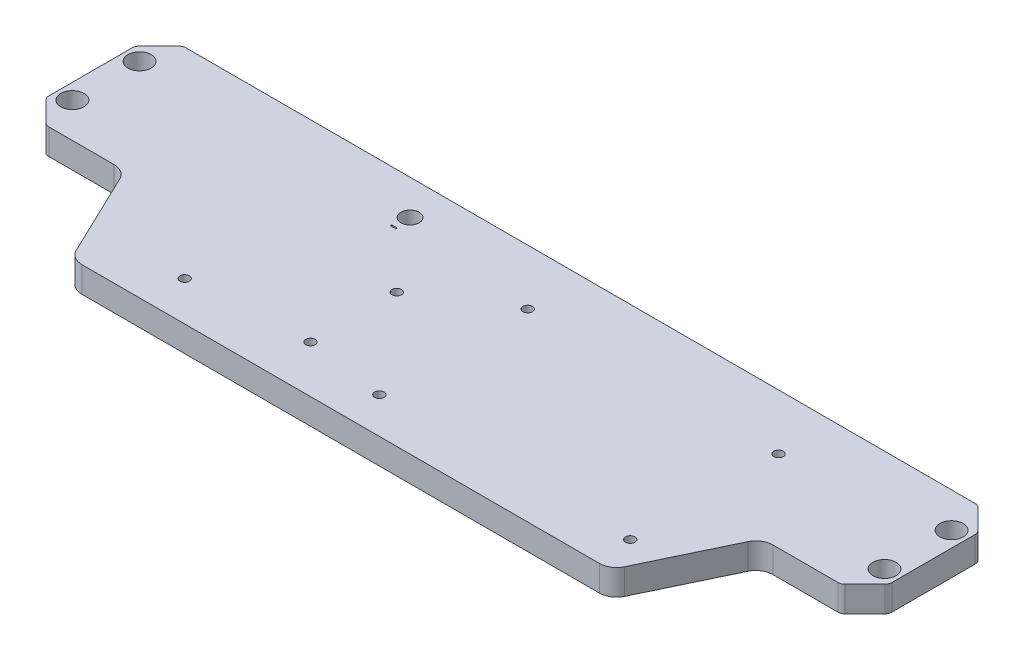
SolidWorks part; units mm, degrees
ref_plane "Front Plane" through (0, 0, 0) normal (0, 0, 1) x (1, 0, 0)
ref_plane "Top Plane" through (0, 0, 0) normal (0, 1, 0) x (1, 0, 0)
ref_plane "Right Plane" through (0, 0, 0) normal (1, 0, 0) x (0, 0, -1)
sketch "Sketch1" plane through (0, 0, 0) normal (0, 1, 0) x (1, 0, 0)
  line L0 (150.5375, 0) -> (-150.5375, 0) construction
  line L1 (0, 19.1523) -> (0, -12.8729) construction
  line L2 (-156.2525, 25.4) -> (-156.2525, -25.4)
  line L3 (-156.2525, 25.4) -> (-118.1525, 25.4)
  line L4 (-118.1525, 25.4) -> (-99.9138, 63.5)
  line L5 (-99.9138, 63.5) -> (99.9138, 63.5)
  line L6 (118.1525, 25.4) -> (99.9138, 63.5)
  line L7 (156.2525, 25.4) -> (118.1525, 25.4)
  line L8 (156.2525, 25.4) -> (156.2525, -25.4)
  line L9 (156.2525, -25.4) -> (118.1525, -25.4)
  line L10 (118.1525, -25.4) -> (99.9138, -63.5)
  line L11 (-118.1525, -25.4) -> (-99.9138, -63.5)
  line L12 (-99.9138, -63.5) -> (99.9138, -63.5)
  line L13 (-156.2525, -25.4) -> (-118.1525, -25.4)
  line L15 (93.9495, -50.1231) -> (93.9495, 4.8769)
  line L16 (93.9495, -50.1231) -> (0.9495, -50.1231)
  line L17 (0.9495, -50.1231) -> (0.9495, 4.8769)
  line L18 (93.9495, 4.8769) -> (0.9495, 4.8769)
  line L19 (93.9495, -50.1231) -> (0.9495, 4.8769) construction
  line L20 (0.9495, -50.1231) -> (93.9495, 4.8769) construction
  line L21 (-28.7505, -45.9849) -> (-28.7505, -13.9809) construction
  line L22 (-118.1525, 25.4) -> (118.1525, 25.4)
  line L23 (-51.267, 6.696) -> (-49.235, 6.696)
  line L24 (-51.267, 6.696) -> (-51.267, 6.188)
  line L25 (-51.267, 6.188) -> (-49.235, 6.188)
  line L26 (-49.235, 6.696) -> (-49.235, 6.188)
  circle A0 centre (-150.5375, 12.446) radius 4.318
  circle A1 centre (-150.5375, -12.446) radius 4.318
  circle A2 centre (150.5375, -12.446) radius 4.318
  circle A3 centre (150.5375, 12.446) radius 4.318
  circle A4 centre (0.9495, -50.1231) radius 1.75
  circle A5 centre (0.9495, 4.8769) radius 1.75
  circle A6 centre (93.9495, 4.8769) radius 1.75
  circle A7 centre (93.9495, -50.1231) radius 1.75
  circle A10 centre (-28.7505, -45.9849) radius 1.75
  circle A11 centre (-28.7505, -13.9809) radius 1.75
  circle A13 centre (-72.4385, -48.9059) radius 1.75
  circle A14 centre (-50.251, 12.446) radius 3.4
  point P4 (0, 0)
  point P18 (-156.2525, 0)
  point P19 (0, 63.5)
  point P48 (0, 0)
  point P57 (-50.251, 6.696)
  dimension "D2" = 8.636
  dimension "D11" = 3.5
  dimension "D13" = 5.75
  dimension "D15" = 3.5
  dimension "D12" = 6.8
  dimension "D1" = 301.075
  dimension "D3" = 12.446
  dimension "D4" = 5.715
  dimension "D5" = 50.8
  dimension "D6" = 63.5
  dimension "D7" = 38.1
  dimension "D8" = 56.3387
  dimension "D9" = 93
  dimension "D10" = 55
  dimension "D14" = 32.004
  dimension "D16" = 43.688
  dimension "D17" = 2.921
  dimension "D18" = 2.032
  dimension "D19" = 0.508
  dimension "D20" = 14.5941
  dimension "D21" = 27.4753
  dimension "D22" = 13.3769
  dimension "D23" = 5.9643
extrude "Boss-Extrude1" add sketch "Sketch1" along normal blind 9.525 contours L2 L13 L11 L12 L10 L9 L8 L7 L6 L5 L4 L3 A7 L16 A4 L17 A5 L18 A6 L15 A1 A0 A2 A3 | A7 L15 A6 L18 A5 L17 A4 L16
fillet "Fillet1" radius 6.35 4 edges at (-118.1525, 4.7625, 25.4) (-99.9138, 4.7625, 63.5) (99.9138, 4.7625, 63.5) (118.1525, 4.7625, 25.4)
chamfer "Chamfer1" distance 8.89 angle 45 4 edges at (156.2525, 4.7625, -25.4) (156.2525, 4.7625, 25.4) (-156.2525, 4.7625, -25.4) (-156.2525, 4.7625, 25.4)
fillet "Fillet2" radius 2.54 8 edges at (-156.2525, 4.7625, -16.51) (-147.3625, 4.7625, -25.4) (-156.2525, 4.7625, 16.51) (-147.3625, 4.7625, 25.4) (147.3625, 4.7625, -25.4) (156.2525, 4.7625, -16.51) (156.2525, 4.7625, 16.51) (147.3625, 4.7625, 25.4)
